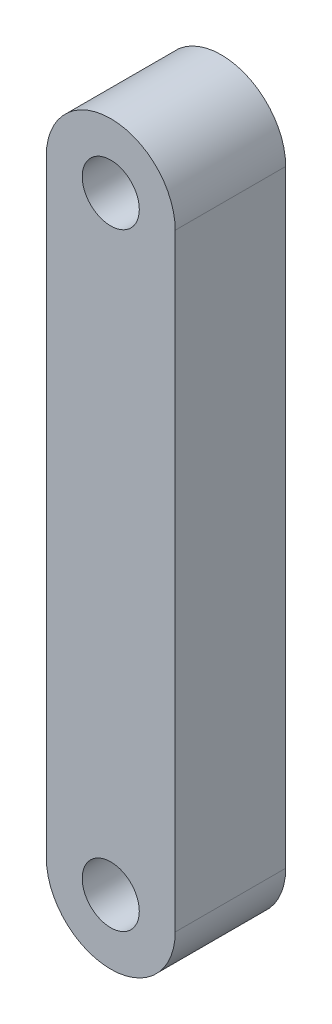
SolidWorks part; units mm, degrees
ref_plane "Płaszczyzna przednia" through (0, 0, 0) normal (0, 0, 1) x (1, 0, 0)
ref_plane "Płaszczyzna górna" through (0, 0, 0) normal (0, 1, 0) x (1, 0, 0)
ref_plane "Płaszczyzna prawa" through (0, 0, 0) normal (1, 0, 0) x (0, 0, -1)
sketch "Szkic1" plane through (0, 0, 0) normal (0, 0, 1) x (1, 0, 0)
  line L0 (1144.9495, -37.2111) -> (1144.9495, -4.2111)
  line L2 (1137.9495, -4.2111) -> (1137.9495, -37.2111)
  arc A1 (1137.9495, -37.2111) -> (1144.9495, -37.2111) centre (1141.4495, -37.2111) ccw
  circle A3 centre (1141.4495, -4.2111) radius 1.55
  circle A5 centre (1141.4495, -37.2111) radius 1.55
  arc A6 (1144.9495, -4.2111) -> (1137.9495, -4.2111) centre (1141.4495, -4.2111) ccw
  dimension "D1" = 7
  dimension "D3" = 33
extrude "Dodanie-wyciągnięcie1" add sketch "Szkic1" along normal blind 6
ref_plane "Płaszczyzna1" through (1141.4495, 0, 0) normal (1, 0, 0) x (0, 0, -1)
sketch "Szkic2" plane through (1141.4495, 0, 0) normal (1, 0, 0) x (0, 0, -1)
  line L0 (0, -20.7111) -> (-5.7585, -20.7111)
  line L8 (-6, -37.2111) -> (0, -37.2111) construction
  dimension "D1" = 16.5
